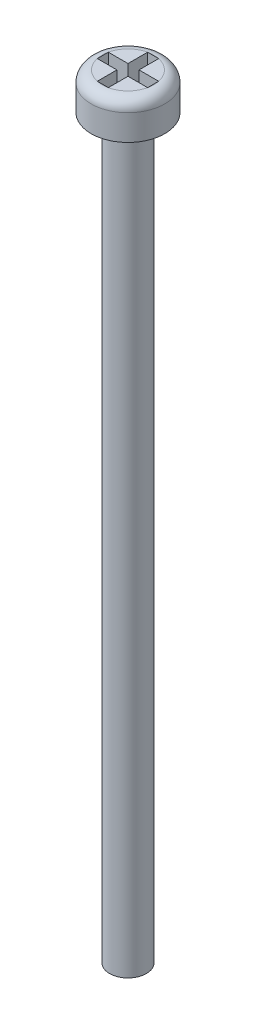
SolidWorks part; units mm, degrees
ref_plane "Front Plane" through (0, 0, 0) normal (0, 0, 1) x (1, 0, 0)
ref_plane "Top Plane" through (0, 0, 0) normal (0, 1, 0) x (1, 0, 0)
ref_plane "Right Plane" through (0, 0, 0) normal (1, 0, 0) x (0, 0, -1)
sketch "Sketch1" plane through (0, 0, 0) normal (0, 1, 0) x (1, 0, 0)
  circle A0 centre (0, 0) radius 0.5
extrude "Boss-Extrude1" add sketch "Sketch1" along normal blind 10 and the other way blind 11
sketch "Sketch2" plane through (0, 10, 0) normal (0, 1, 0) x (1, 0, 0)
  circle A0 centre (0, 0) radius 1
extrude "Boss-Extrude2" add sketch "Sketch2" against normal blind 1
fillet "Fillet1" radius 0.3 1 edges at (0, 10, 1)
sketch "Sketch3" plane through (0, 10, 0) normal (0, 1, 0) x (1, 0, 0)
  line L0 (-0.15, 0.15) -> (-0.15, 0.6837)
  line L1 (-0.6837, -0.15) -> (-0.15, -0.15)
  line L2 (-0.6837, -0.15) -> (-0.6837, 0.15)
  line L3 (-0.6837, 0.15) -> (-0.15, 0.15)
  line L4 (0.6837, -0.15) -> (0.6837, 0.15)
  line L7 (-0.15, -0.6837) -> (0.15, -0.6837)
  line L8 (-0.15, -0.6837) -> (-0.15, -0.15)
  line L9 (-0.15, 0.6837) -> (0.15, 0.6837)
  line L10 (0.15, -0.6837) -> (0.15, -0.15)
  line L12 (0.15, -0.15) -> (0.6837, -0.15)
  line L15 (0.15, 0.15) -> (0.15, 0.6837)
  line L18 (0.15, 0.15) -> (0.6837, 0.15)
  circle A0 centre (0, 0) radius 0.7 construction
  point P0 (0, 0)
  point P8 (0, 0)
  dimension "D1" = 0.3
  dimension "D2" = 0.3
extrude "Cut-Extrude1" cut sketch "Sketch3" against normal blind 0.6
